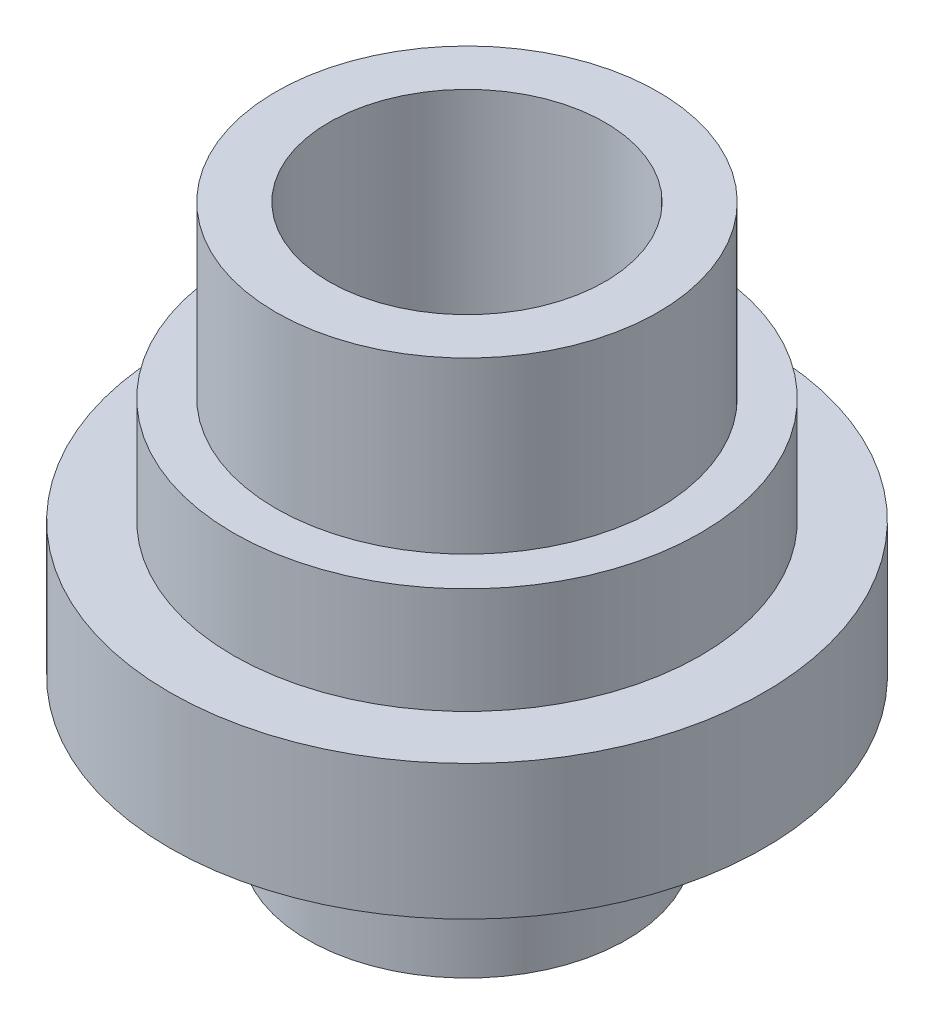
SolidWorks part; units mm, degrees
ref_plane "Plan de face" through (0, 0, 0) normal (0, 0, 1) x (1, 0, 0)
ref_plane "Plan de dessus" through (0, 0, 0) normal (0, 1, 0) x (1, 0, 0)
ref_plane "Plan de droite" through (0, 0, 0) normal (1, 0, 0) x (0, 0, -1)
sketch "Esquisse1" plane through (0, 0, 0) normal (0, 1, 0) x (1, 0, 0)
  circle A0 centre (0, 0) radius 11
  dimension "D1" = 22
extrude "Boss.-Extru.1" add sketch "Esquisse1" along normal blind 5
sketch "Esquisse2" plane through (0, 5, 0) normal (0, 1, 0) x (1, 0, 0)
  circle A0 centre (0, 0) radius 9
  dimension "D1" = 18
extrude "Boss.-Extru.2" add sketch "Esquisse2" along normal blind 8
sketch "Esquisse3" plane through (0, 0, 0) normal (0, -1, 0) x (1, 0, 0)
  circle A0 centre (0, 0) radius 14
  dimension "D1" = 28
extrude "Boss.-Extru.3" add sketch "Esquisse3" along normal blind 6.35
sketch "Esquisse4" plane through (0, -6.35, 0) normal (0, -1, 0) x (1, 0, 0)
  line L2 (1.775, -2.0345) -> (1.775, 2.0345)
  line L4 (-1.775, -2.0345) -> (-1.775, 2.0345)
  line L5 (1.775, -2.7) -> (-1.775, 2.7) construction
  line L6 (1.775, 2.7) -> (-1.775, -2.7) construction
  arc A0 (1.775, 2.0345) -> (-1.775, 2.0345) centre (0, 0) ccw
  arc A1 (-1.775, -2.0345) -> (1.775, -2.0345) centre (0, 0) ccw
  circle A2 centre (0, 0) radius 7.5
  dimension "D1" = 5.4
  dimension "D6" = 15
  dimension "D2" = 3.55
  dimension "D3" = 5.4
  dimension "D4" = 4.0691
  dimension "D5" = 4.0691
extrude "Boss.-Extru.5" add sketch "Esquisse4" along normal blind 7
sketch "Esquisse5" plane through (0, -6.35, 0) normal (0, -1, 0) x (1, 0, 0)
  circle A0 centre (0, 0) radius 1.25
  dimension "D1" = 2.5
extrude "Enlèv. mat.-Extru.1" cut sketch "Esquisse5" against normal through all both and the other way through all
sketch "Esquisse6" plane through (0, 13, 0) normal (0, 1, 0) x (1, 0, 0)
  circle A0 centre (0, 0) radius 6.5
  dimension "D1" = 13
extrude "Enlèv. mat.-Extru.2" cut sketch "Esquisse6" against normal blind 13
fillet "Congé3" radius 2 1 edges at (0, -6.35, -7.5)
fillet "Congé2" [suppressed] radius 0.5
fillet "Congé1" [suppressed] radius 0.5
